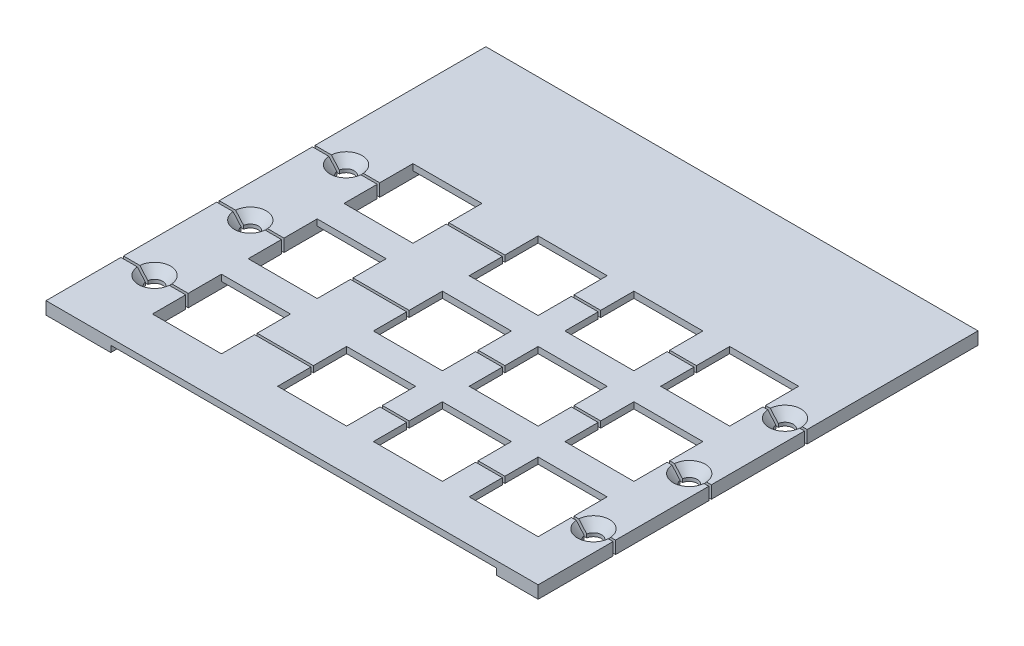
SolidWorks part; units mm, degrees
ref_plane "Front" through (0, 0, 0) normal (0, 0, 1) x (1, 0, 0)
ref_plane "Top" through (0, 0, 0) normal (0, 1, 0) x (1, 0, 0)
ref_plane "Right" through (0, 0, 0) normal (1, 0, 0) x (0, 0, -1)
sketch "Sketch1" plane through (0, 0, 0) normal (0, 1, 0) x (1, 0, 0)
  line L0 (2.6035, 2.6797) -> (8.0137, 2.6797) construction
  line L1 (-49.7332, -44.45) -> (49.7332, -44.45)
  line L2 (-49.7332, -44.45) -> (-49.7332, 44.45)
  line L3 (-49.7332, 44.45) -> (49.7332, 44.45)
  line L4 (49.7332, -44.45) -> (49.7332, 44.45)
  line L5 (-49.7332, -44.45) -> (49.7332, 44.45) construction
  line L6 (-49.7332, 44.45) -> (49.7332, -44.45) construction
  line L7 (-11.3411, 16.6243) -> (2.6035, 16.6243)
  line L8 (-11.3411, 16.6243) -> (-11.3411, 2.6797)
  line L9 (-11.3411, 2.6797) -> (2.6035, 2.6797)
  line L10 (2.6035, 16.6243) -> (2.6035, 2.6797)
  line L11 (8.0137, 16.6243) -> (21.9583, 16.6243)
  line L12 (8.0137, 16.6243) -> (8.0137, 2.6797)
  line L13 (8.0137, 2.6797) -> (21.9583, 2.6797)
  line L14 (21.9583, 16.6243) -> (21.9583, 2.6797)
  line L15 (27.3685, 16.6243) -> (41.3131, 16.6243)
  line L16 (27.3685, 16.6243) -> (27.3685, 2.6797)
  line L17 (27.3685, 2.6797) -> (41.3131, 2.6797)
  line L18 (41.3131, 16.6243) -> (41.3131, 2.6797)
  line L19 (21.9583, 2.6797) -> (27.3685, 2.6797) construction
  line L20 (2.6035, 2.6797) -> (2.6035, -2.7305) construction
  line L21 (-11.3411, -2.7305) -> (2.6035, -2.7305)
  line L22 (-11.3411, -2.7305) -> (-11.3411, -16.6751)
  line L23 (-11.3411, -16.6751) -> (2.6035, -16.6751)
  line L24 (2.6035, -2.7305) -> (2.6035, -16.6751)
  line L25 (8.0137, -2.7305) -> (21.9583, -2.7305)
  line L26 (8.0137, -2.7305) -> (8.0137, -16.6751)
  line L27 (8.0137, -16.6751) -> (21.9583, -16.6751)
  line L28 (21.9583, -2.7305) -> (21.9583, -16.6751)
  line L29 (27.3685, -2.7305) -> (41.3131, -2.7305)
  line L30 (27.3685, -2.7305) -> (27.3685, -16.6751)
  line L31 (27.3685, -16.6751) -> (41.3131, -16.6751)
  line L32 (41.3131, -2.7305) -> (41.3131, -16.6751)
  line L33 (21.9583, 2.6797) -> (21.9583, -2.7305) construction
  line L34 (41.3131, 2.6797) -> (41.3131, -2.7305) construction
  line L35 (2.6035, -22.0853) -> (2.6035, -16.6751) construction
  line L36 (-11.3411, -22.0853) -> (2.6035, -22.0853)
  line L37 (-11.3411, -22.0853) -> (-11.3411, -36.0299)
  line L38 (-11.3411, -36.0299) -> (2.6035, -36.0299)
  line L39 (2.6035, -22.0853) -> (2.6035, -36.0299)
  line L40 (8.0137, -22.0853) -> (21.9583, -22.0853)
  line L41 (8.0137, -22.0853) -> (8.0137, -36.0299)
  line L42 (8.0137, -36.0299) -> (21.9583, -36.0299)
  line L43 (21.9583, -22.0853) -> (21.9583, -36.0299)
  line L44 (27.3685, -22.0853) -> (41.3131, -22.0853)
  line L45 (27.3685, -22.0853) -> (27.3685, -36.0299)
  line L46 (27.3685, -36.0299) -> (41.3131, -36.0299)
  line L47 (41.3131, -22.0853) -> (41.3131, -36.0299)
  line L48 (21.9583, -22.0853) -> (21.9583, -16.6751) construction
  line L49 (41.3131, -16.6751) -> (41.3131, -22.0853) construction
  line L50 (41.3131, -36.0299) -> (49.7332, -36.0299) construction
  line L51 (-13.4112, 0.6096) -> (4.6736, 0.6096) construction
  line L52 (-13.4112, 0.6096) -> (-13.4112, 18.6944) construction
  line L53 (-13.4112, 18.6944) -> (4.6736, 18.6944) construction
  line L54 (4.6736, 0.6096) -> (4.6736, 18.6944) construction
  line L55 (-13.4112, 0.6096) -> (4.6736, 18.6944) construction
  line L56 (-13.4112, 18.6944) -> (4.6736, 0.6096) construction
  line L57 (24.0284, 0.6096) -> (5.9436, 0.6096) construction
  line L58 (24.0284, 0.6096) -> (24.0284, 18.6944) construction
  line L59 (24.0284, 18.6944) -> (5.9436, 18.6944) construction
  line L60 (5.9436, 0.6096) -> (5.9436, 18.6944) construction
  line L61 (24.0284, 0.6096) -> (5.9436, 18.6944) construction
  line L62 (24.0284, 18.6944) -> (5.9436, 0.6096) construction
  line L63 (41.3131, -36.0299) -> (41.3131, -44.45) construction
  line L64 (34.3408, 16.6243) -> (34.3408, 9.652) construction
  line L65 (-36.6395, 2.6797) -> (-22.6949, 2.6797)
  line L66 (-36.6395, 2.6797) -> (-36.6395, 16.6243)
  line L67 (-36.6395, 16.6243) -> (-22.6949, 16.6243)
  line L68 (-22.6949, 2.6797) -> (-22.6949, 16.6243)
  line L69 (-36.6395, 2.6797) -> (-22.6949, 16.6243) construction
  line L70 (-36.6395, 16.6243) -> (-22.6949, 2.6797) construction
  line L71 (-36.6395, -16.6751) -> (-22.6949, -16.6751)
  line L72 (-36.6395, -16.6751) -> (-36.6395, -2.7305)
  line L73 (-36.6395, -2.7305) -> (-22.6949, -2.7305)
  line L74 (-22.6949, -16.6751) -> (-22.6949, -2.7305)
  line L75 (-36.6395, -16.6751) -> (-22.6949, -2.7305) construction
  line L76 (-36.6395, -2.7305) -> (-22.6949, -16.6751) construction
  line L77 (-36.6395, -36.0299) -> (-22.6949, -36.0299)
  line L78 (-36.6395, -36.0299) -> (-36.6395, -22.0853)
  line L79 (-36.6395, -22.0853) -> (-22.6949, -22.0853)
  line L80 (-22.6949, -36.0299) -> (-22.6949, -22.0853)
  line L81 (-36.6395, -36.0299) -> (-22.6949, -22.0853) construction
  line L82 (-36.6395, -22.0853) -> (-22.6949, -36.0299) construction
  line L83 (-43.3832, 18.6563) -> (-15.9512, 18.6563) construction
  line L84 (-43.3832, 18.6563) -> (-43.3832, 0.6477) construction
  line L85 (-43.3832, 0.6477) -> (-15.9512, 0.6477) construction
  line L86 (-15.9512, 18.6563) -> (-15.9512, 0.6477) construction
  line L87 (-43.3832, 18.6563) -> (-15.9512, 0.6477) construction
  line L88 (-43.3832, 0.6477) -> (-15.9512, 18.6563) construction
  line L89 (-43.3832, -0.6985) -> (-15.9512, -0.6985) construction
  line L90 (-43.3832, -0.6985) -> (-43.3832, -18.7071) construction
  line L91 (-43.3832, -18.7071) -> (-15.9512, -18.7071) construction
  line L92 (-15.9512, -0.6985) -> (-15.9512, -18.7071) construction
  line L93 (-43.3832, -0.6985) -> (-15.9512, -18.7071) construction
  line L94 (-43.3832, -18.7071) -> (-15.9512, -0.6985) construction
  line L95 (-43.3832, -20.0533) -> (-15.9512, -20.0533)
  line L96 (-43.3832, -20.0533) -> (-43.3832, -38.0619) construction
  line L97 (-43.3832, -38.0619) -> (-15.9512, -38.0619) construction
  line L98 (-15.9512, -20.0533) -> (-15.9512, -38.0619) construction
  line L99 (-43.3832, -20.0533) -> (-15.9512, -38.0619) construction
  line L100 (-43.3832, -38.0619) -> (-15.9512, -20.0533) construction
  line L101 (25.2984, 0.6096) -> (43.3832, 0.6096) construction
  line L102 (25.2984, 0.6096) -> (25.2984, 18.6944) construction
  line L103 (25.2984, 18.6944) -> (43.3832, 18.6944) construction
  line L104 (43.3832, 0.6096) -> (43.3832, 18.6944) construction
  line L105 (25.2984, 0.6096) -> (43.3832, 18.6944) construction
  line L106 (25.2984, 18.6944) -> (43.3832, 0.6096) construction
  point P0 (0, 0)
  point P42 (14.986, 9.652)
  point P43 (-4.3688, 9.652)
  point P49 (-4.3688, 16.6243)
  point P51 (-11.3411, 9.652)
  point P54 (-29.6672, 9.652)
  point P55 (14.986, 16.6243)
  point P57 (8.0137, 9.652)
  point P63 (-29.6672, -9.7028)
  point P68 (-29.6672, -29.0576)
  point P73 (-29.6672, -9.7028)
  point P75 (-29.6672, 9.652)
  point P83 (-29.6672, -29.0576)
  point P89 (34.3408, 9.652)
  point P95 (0, 0)
  point P96 (0, 0)
  point P97 (0, 0)
  dimension "D1" = 88.9
  dimension "D2" = 6.35
  dimension "D3" = 13.9446
  dimension "D4" = 18.0848
  dimension "D5" = 1.27
  dimension "D6" = 6.35
  dimension "D7" = 18.0086
  dimension "D8" = 27.432
  dimension "D9" = 2.54
extrude "Boss-Extrude1" add sketch "Sketch1" along normal blind 1.27
sketch "Sketch2" plane through (0, 1.27, 0) normal (0, 1, 0) x (1, 0, 0)
  line L0 (-49.7332, 9.652) -> (49.7332, 9.652)
  line L1 (-49.7332, -44.45) -> (-49.7332, 44.45) construction
  line L2 (49.7332, -44.45) -> (49.7332, 44.45) construction
  line L3 (27.3685, 16.6243) -> (27.3685, 2.6797) construction
  line L4 (-49.7332, -9.7028) -> (49.7332, -9.7028)
  line L5 (41.3131, -2.7305) -> (41.3131, -16.6751) construction
  line L6 (41.3131, -22.0853) -> (41.3131, -36.0299) construction
  line L7 (-49.7332, -29.0576) -> (49.7332, -29.0576)
  point P8 (27.3685, 9.652)
  point P15 (41.3131, -9.7028)
  point P18 (41.3131, -29.0576)
sketch "Sketch4" plane through (0, 1.27, 0) normal (0, 1, 0) x (1, 0, 0)
  line L0 (-49.7332, 9.652) -> (49.7332, 9.652) construction
  line L1 (-49.7332, -9.7028) -> (49.7332, -9.7028) construction
  line L2 (-49.7332, -29.0576) -> (49.7332, -29.0576) construction
  line L3 (2.6035, 16.6243) -> (8.0137, 16.6243) construction
  line L4 (21.9583, 16.6243) -> (27.3685, 16.6243) construction
  line L5 (-22.6949, 16.6243) -> (-11.3411, 16.6243) construction
  line L6 (41.3131, 16.6243) -> (49.7332, 16.6243) construction
  line L7 (49.7332, -44.45) -> (49.7332, 44.45) construction
  line L8 (-36.6395, 16.6243) -> (-49.7332, 16.6243) construction
  line L9 (-49.7332, -44.45) -> (-49.7332, 44.45) construction
  point P0 (-17.018, 9.652)
  point P1 (-17.018, -9.7028)
  point P4 (-17.018, -29.0576)
  point P7 (5.3086, -29.0576)
  point P10 (5.3086, -9.7028)
  point P11 (5.3086, 9.652)
  point P12 (24.6634, 9.652)
  point P13 (24.6634, -9.7028)
  point P14 (24.6634, -29.0576)
  point P15 (45.5232, 9.652)
  point P16 (45.5232, -9.7028)
  point P17 (45.5232, -29.0576)
  point P18 (-43.1864, 9.652)
  point P19 (-43.1864, -9.7028)
  point P20 (-43.1864, -29.0576)
  point P43 (5.3086, 16.6243)
  point P44 (24.6634, 16.6243)
  point P45 (-43.1864, 16.6243)
  point P46 (-17.018, 16.6243)
  point P47 (45.5232, 16.6243)
sketch "Sketch6" plane through (0, 0, 0) normal (0, -1, 0) x (1, 0, 0)
  line L0 (-49.7332, -44.45) -> (49.7332, -44.45) construction
  line L1 (-49.7332, 44.45) -> (-36.6395, 44.45)
  line L2 (-49.7332, 44.45) -> (-49.7332, -44.45)
  line L3 (-49.7332, -44.45) -> (-36.6395, -44.45)
  line L4 (-36.6395, 44.45) -> (-36.6395, -44.45)
  line L5 (-49.7332, 44.45) -> (49.7332, 44.45) construction
  line L6 (41.3131, 44.45) -> (49.7332, 44.45)
  line L7 (41.3131, 44.45) -> (41.3131, -44.45)
  line L8 (41.3131, -44.45) -> (49.7332, -44.45)
  line L9 (49.7332, 44.45) -> (49.7332, -44.45)
  line L10 (41.3131, 22.0853) -> (41.3131, 36.0299) construction
  line L11 (-36.6395, 36.0299) -> (-36.6395, 22.0853) construction
extrude "Boss-Extrude2" add sketch "Sketch6" along normal blind 1.27
extrude "Cut-Extrude-Thin2" cut sketch "Sketch2" against normal through all thin thin type mid plane wall 0.508
hole_wizard "CSK for #4 Flat Head Socket Cap Screw1" positions "3DSketch2" profile "Sketch7" countersink size "#4" standard "ANSI Inch" end condition up to next
sketch3d "3DSketch2"
  point P0 (-43.1864, 1.27, -9.652)
  point P3 (-43.1864, 1.27, 9.7028)
  point P6 (-43.1864, 1.27, 29.0576)
  point P9 (45.5232, 1.27, -9.652)
  point P12 (45.5232, 1.27, 9.7028)
  point P15 (45.5232, 1.27, 29.0576)
sketch "Sketch7" plane through (-43.1864, 1.27, -9.652) normal (1, 0, 0) x (0, 0, 1)
  line L0 (0, 0) -> (0, 2.54)
  line L1 (0, 2.54) -> (1.632, 2.54)
  line L2 (1.632, 2.54) -> (1.6319, 1.8481)
  line L3 (1.6319, 1.8481) -> (3.2385, 0)
  line L5 (3.2385, 0) -> (0, 0)
  line L6 (-1.632, 1.8481) -> (-3.2385, 0) construction
  line L11 (0, -6.35) -> (0, 107.95) construction
  dimension "Thru Hole Dia." = 3.2639
  dimension "Thru Hole Depth" = 2.54
  dimension "Near C'Sink Dia." = 6.477
  dimension "Near C'Sink Angle" = 82
